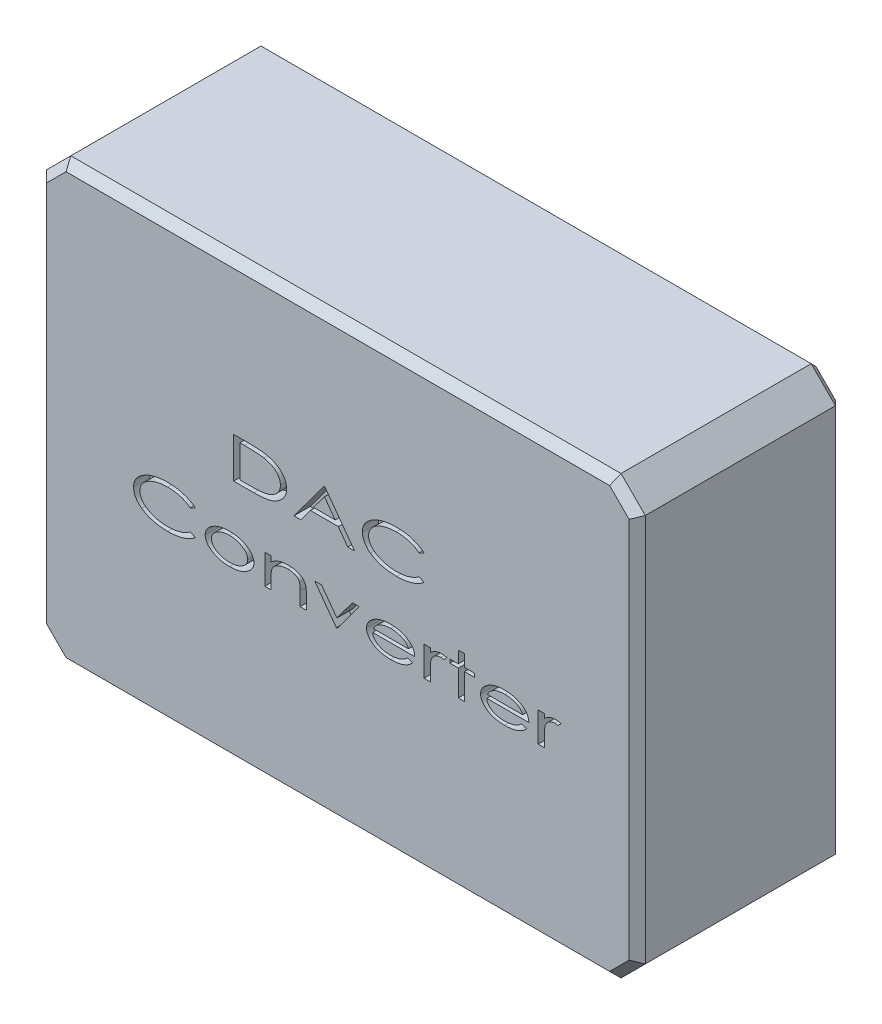
SolidWorks part; units mm, degrees
material "ABS"
ref_plane "Front Plane" through (0, 0, 0) normal (0, 0, 1) x (1, 0, 0)
ref_plane "Top Plane" through (0, 0, 0) normal (0, 1, 0) x (1, 0, 0)
ref_plane "Right Plane" through (0, 0, 0) normal (1, 0, 0) x (0, 0, -1)
sketch "Sketch1" plane through (0, 0, 0) normal (0, 0, 1) x (1, 0, 0)
  line L1 (0, 0) -> (74, 0)
  line L2 (0, 0) -> (0, 54)
  line L3 (0, 54) -> (74, 54)
  line L4 (74, 0) -> (74, 54)
  dimension "D1" = 74
  dimension "D2" = 54
extrude "Boss-Extrude1" add sketch "Sketch1" along normal blind 25.5 contours L3 L4 L1 L2
chamfer "Chamfer1" distance 3 angle 45 4 edges at (0, 0, 12.75) (74, 0, 12.75) (0, 54, 12.75) (74, 54, 12.75)
chamfer "Chamfer2" distance 1 angle 45 16 edges at (72.5, 1.5, 0) (74, 27, 0) (72.5, 52.5, 0) (37, 54, 0) (1.5, 52.5, 0) (0, 27, 0) (1.5, 1.5, 0) (37, 0, 0) (1.5, 52.5, 25.5) (37, 54, 25.5) (72.5, 52.5, 25.5) (74, 27, 25.5) (72.5, 1.5, 25.5) (37, 0, 25.5) (1.5, 1.5, 25.5) (0, 27, 25.5)
sketch "Sketch2" plane through (0, 0, 25.5) normal (0, 0, 1) x (1, 0, 0)
  text T0 "    DAC \r\nConverter" font "Century Gothic" height 5
extrude "Cut-Extrude1" cut sketch "Sketch2" against normal blind 2
